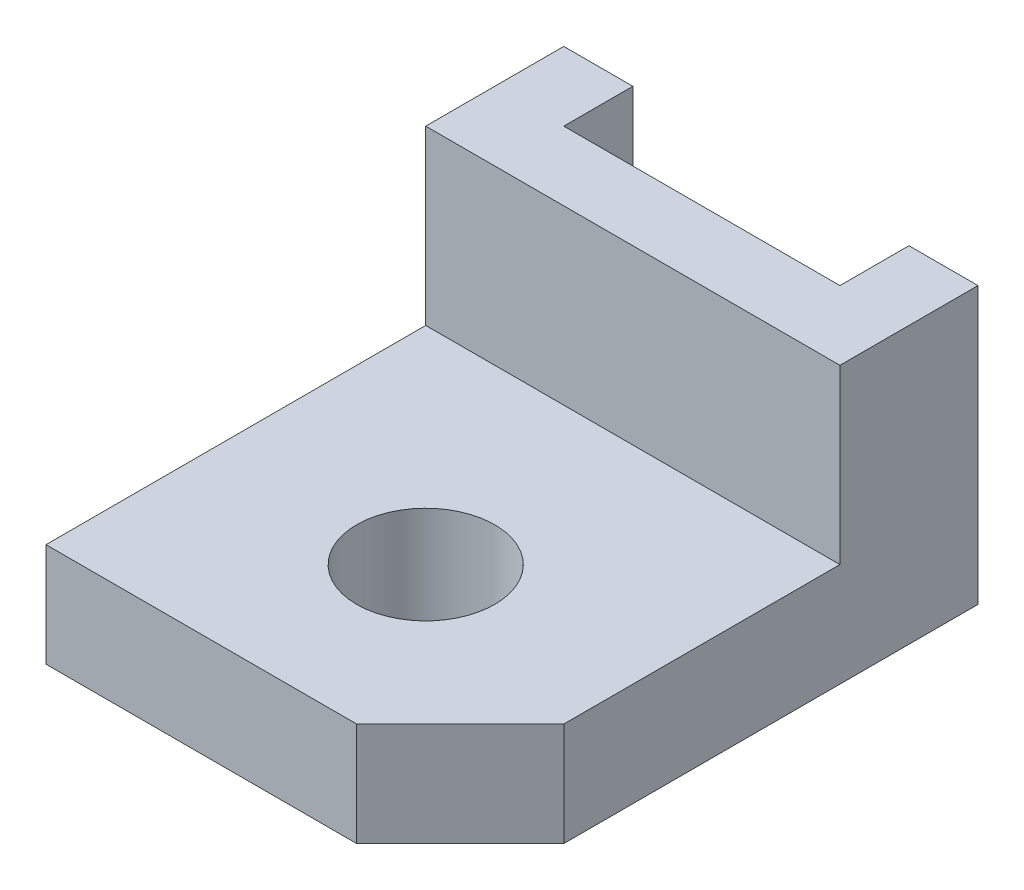
SolidWorks part; units mm, degrees
ref_plane "Front Plane" through (0, 0, 0) normal (1, 0, 0) x (0, 1, 0)
ref_plane "Top Plane" through (0, 0, 0) normal (0, 0, 1) x (0, 1, 0)
ref_plane "Right Plane" through (0, 0, 0) normal (0, 1, 0) x (-1, 0, 0)
sketch "Sketch1" plane through (0, 0, 0) normal (0, 1, 0) x (-1, 0, 0)
  line L0 (-30, -50) -> (30, -50)
  line L1 (30, -50) -> (30, 25)
  line L2 (0, 0) -> (50000, 0) construction
  line L3 (0, 0) -> (0, 50000) construction
  line L4 (30, 25) -> (-15, 25)
  line L5 (-30, 10) -> (-30, -50)
  line L6 (-15, 25) -> (-30, 10)
  circle A0 centre (0, 0) radius 10
  point P5 (-30, 25)
  point P13 (0, 0)
  point P15 (40.5083, 28.7255)
  point P16 (10.6277, 4.3897)
  dimension "D1" = 20
  dimension "D2" = 75
  dimension "D3" = 60
  dimension "D4" = 30
  dimension "D5" = 25
extrude "Boss-Extrude1" add sketch "Sketch1" along normal blind 15
sketch "Sketch2" plane through (0, 15, 0) normal (0, 1, 0) x (-1, 0, 0)
  line L0 (-30, -50) -> (-30, -30)
  line L1 (-30, 10) -> (-30, -50) construction
  line L2 (-30, -30) -> (30, -30)
  line L3 (30, -50) -> (30, 25) construction
  line L4 (30, -30) -> (30, -50)
  line L5 (30, -50) -> (20, -50)
  line L6 (-30, -50) -> (30, -50) construction
  line L7 (20, -50) -> (20, -40)
  line L8 (20, -40) -> (-20, -40)
  line L9 (-20, -40) -> (-20, -50)
  line L10 (-20, -50) -> (-30, -50)
  line L11 (0, 0) -> (0, -50000) construction
  line L12 (0, 0) -> (50000, 0) construction
  point P5 (-20, -45)
  dimension "D1" = 10
  dimension "D2" = 20
  dimension "D3" = 40
extrude "Boss-Extrude2" add sketch "Sketch2" along normal blind 25
sketch "Sketch3" plane through (0, 40, 0) normal (0, 1, 0) x (-1, 0, 0)
  line L0 (-20, -40) -> (-20, -50)
  line L1 (-20, -50) -> (20, -50)
  line L2 (20, -50) -> (20, -40)
  line L3 (20, -40) -> (-20, -40)
extrude "Cut-Extrude1" cut sketch "Sketch3" against normal through all
